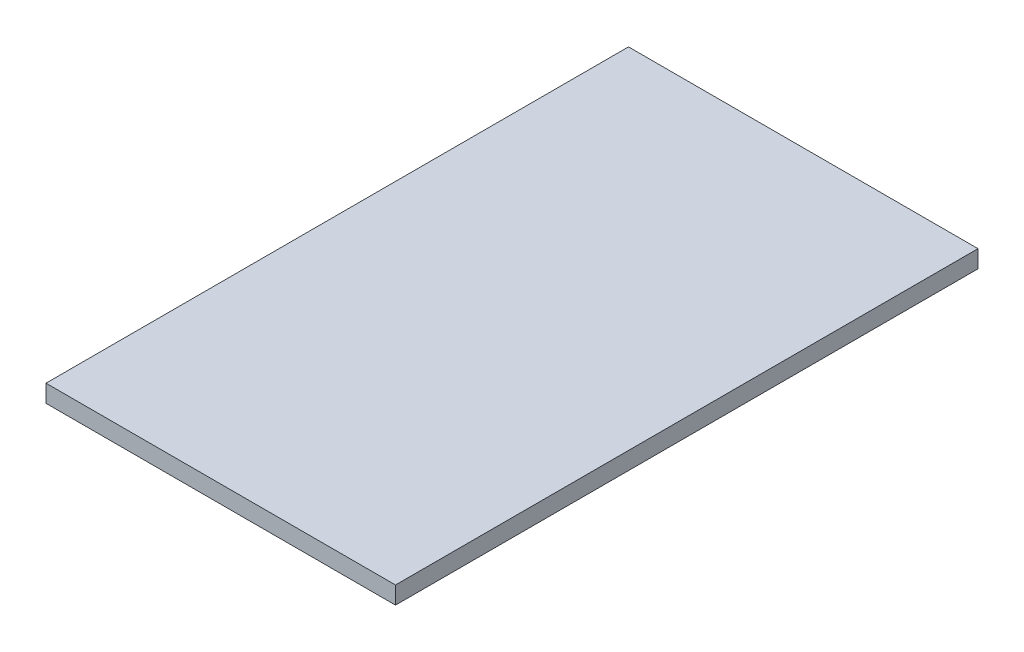
SolidWorks part; units mm, degrees
ref_plane "Front Plane" through (0, 0, 0) normal (0, 0, 1) x (1, 0, 0)
ref_plane "Top Plane" through (0, 0, 0) normal (0, 1, 0) x (1, 0, 0)
ref_plane "Right Plane" through (0, 0, 0) normal (1, 0, 0) x (0, 0, -1)
sketch "Sketch1" plane through (0, 0, 0) normal (0, 1, 0) x (1, 0, 0)
  line L1 (-300, 500) -> (300, 500)
  line L2 (-300, 500) -> (-300, -500)
  line L3 (-300, -500) -> (300, -500)
  line L4 (300, 500) -> (300, -500)
  line L5 (-300, 500) -> (300, -500) construction
  line L6 (-300, -500) -> (300, 500) construction
  point P0 (0, 0)
  dimension "D1" = 600
  dimension "D2" = 1000
extrude "Boss-Extrude1" add sketch "Sketch1" along normal blind 30
